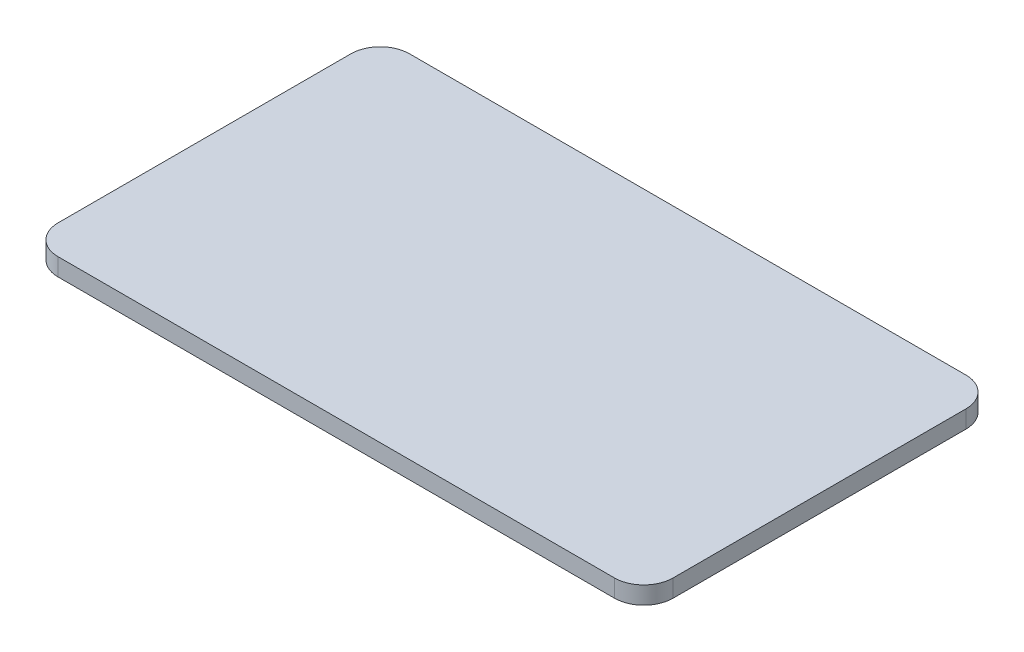
SolidWorks part; units mm, degrees
ref_plane "Front Plane" through (0, 0, 0) normal (0, 0, 1) x (1, 0, 0)
ref_plane "Top Plane" through (0, 0, 0) normal (0, 1, 0) x (1, 0, 0)
ref_plane "Right Plane" through (0, 0, 0) normal (1, 0, 0) x (0, 0, -1)
sketch "Sketch1" plane through (0, 0, 0) normal (0, 1, 0) x (1, 0, 0)
  line L1 (47.5, -30) -> (-47.5, -30)
  line L2 (52.5, -25) -> (52.5, 25)
  line L3 (47.5, 30) -> (-47.5, 30)
  line L4 (-52.5, -25) -> (-52.5, 25)
  line L5 (52.5, -30) -> (-52.5, 30) construction
  line L6 (52.5, 30) -> (-52.5, -30) construction
  arc A0 (47.5, -30) -> (52.5, -25) centre (47.5, -25) ccw
  arc A1 (52.5, 25) -> (47.5, 30) centre (47.5, 25) ccw
  arc A2 (-47.5, -30) -> (-52.5, -25) centre (-47.5, -25) cw
  arc A3 (-47.5, 30) -> (-52.5, 25) centre (-47.5, 25) ccw
  point P0 (0, 0)
  dimension "D3" = 5
  dimension "D1" = 105
  dimension "D2" = 60
extrude "Boss-Extrude1" add sketch "Sketch1" along normal blind 3
